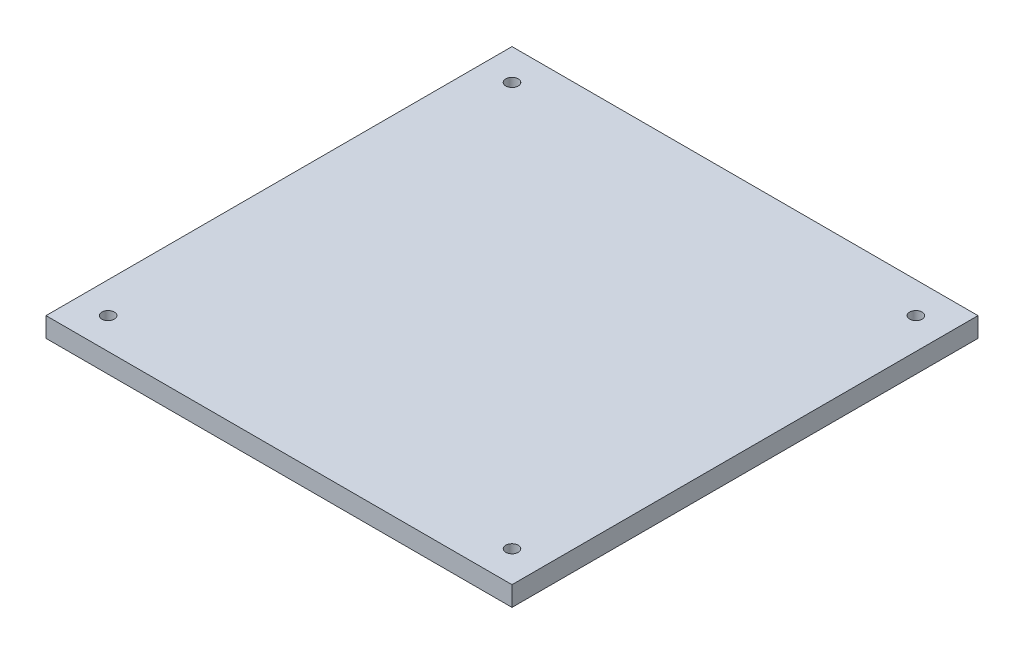
SolidWorks part; units mm, degrees
ref_plane "Front Plane" through (0, 0, 0) normal (0, 0, 1) x (1, 0, 0)
ref_plane "Top Plane" through (0, 0, 0) normal (0, 1, 0) x (1, 0, 0)
ref_plane "Right Plane" through (0, 0, 0) normal (1, 0, 0) x (0, 0, -1)
sketch "Esboço1" plane through (0, 0, 0) normal (0, 1, 0) x (1, 0, 0)
  line L1 (-300, -300) -> (300, -300)
  line L2 (-300, -300) -> (-300, 300)
  line L3 (-300, 300) -> (300, 300)
  line L4 (300, -300) -> (300, 300)
  line L5 (-300, -300) -> (300, 300) construction
  line L6 (-300, 300) -> (300, -300) construction
  point P0 (0, 0)
  dimension "D1" = 600
  dimension "D2" = 600
extrude "Ressalto-extrusão1" add sketch "Esboço1" along normal blind 25.4
sketch "Esboço2" plane through (0, 25.4, 0) normal (0, 1, 0) x (1, 0, 0)
  line L0 (300, 300) -> (-300, 300) construction
  line L1 (-260, -260) -> (260, -260) construction
  line L2 (-260, -260) -> (-260, 260) construction
  line L3 (-260, 260) -> (260, 260) construction
  line L4 (260, -260) -> (260, 260) construction
  line L5 (-260, -260) -> (260, 260) construction
  line L6 (-260, 260) -> (260, -260) construction
  line L7 (-300, 300) -> (-300, -300) construction
  point P0 (0, 0)
  dimension "D1" = 40
  dimension "D2" = 40
hole_wizard "Furo de diâmetro Ø16.0 (16)1" positions "Esboço3" profile "Esboço4" hole size "Ø16.0" standard "Ansi Metric" end condition through all
sketch "Esboço3" plane through (0, 25.4, 0) normal (0, 1, 0) x (1, 0, 0)
  point P0 (-260, 260)
  point P3 (260, 260)
  point P6 (260, -260)
  point P9 (-260, -260)
sketch "Esboço4" plane through (-260, 25.4, -260) normal (1, 0, 0) x (0, 0, 1)
  line L0 (0, 0) -> (0, 25.4)
  line L1 (0, 25.4) -> (8, 25.4)
  line L2 (8, 25.4) -> (8, 0)
  line L5 (8, 0) -> (0, 0)
  line L11 (0, -6.35) -> (0, 107.95) construction
  dimension "Thru Hole Dia." = 16
  dimension "Thru Hole Depth" = 25.4
sketch "Esboço5" plane through (0, 25.4, 0) normal (0, 1, 0) x (1, 0, 0)
  line L0 (-300, 300) -> (300, -300) construction
  line L1 (300, 300) -> (-300, -300) construction
  line L2 (-254.0381, -218.6827) -> (-218.6827, -254.0381) construction
  line L3 (-254.0381, 218.6827) -> (-218.6827, 254.0381) construction
  line L4 (254.0381, 218.6827) -> (218.6827, 254.0381) construction
  line L5 (218.6827, -254.0381) -> (254.0381, -218.6827) construction
  point P16 (236.3604, 236.3604)
  point P17 (-236.3604, 236.3604)
  point P18 (236.3604, -236.3604)
  point P19 (-236.3604, -236.3604)
  dimension "D1" = 50
  dimension "D2" = 90
  dimension "D3" = 90
  dimension "D4" = 90
  dimension "D5" = 90
